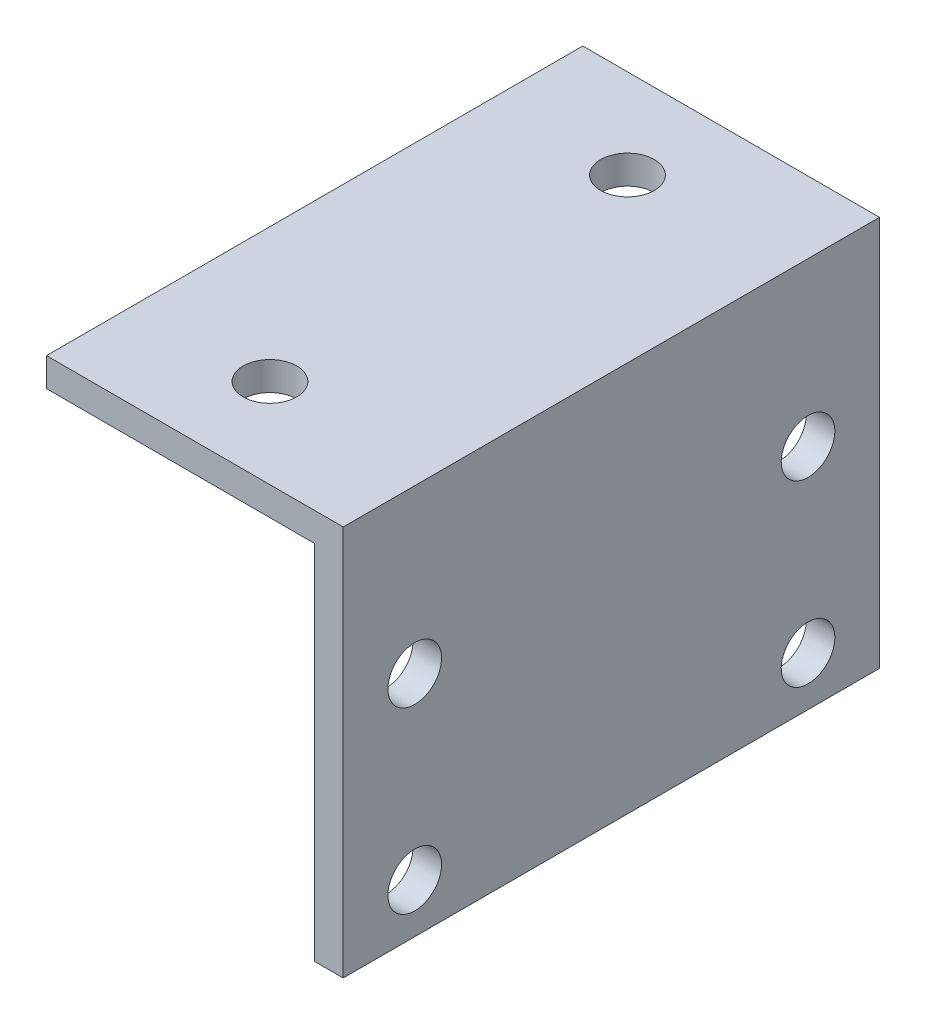
SolidWorks part; units mm, degrees
ref_plane "Front Plane" through (0, 0, 0) normal (0, 0, 1) x (1, 0, 0)
ref_plane "Top Plane" through (0, 0, 0) normal (0, 1, 0) x (1, 0, 0)
ref_plane "Right Plane" through (0, 0, 0) normal (1, 0, 0) x (0, 0, -1)
sketch "Sketch1" plane through (0, 0, 0) normal (0, 0, 1) x (1, 0, 0)
  line L0 (0, 0) -> (-23.4, 0)
  line L1 (-23.4, 0) -> (-23.4, 1.6)
  line L2 (-23.4, 1.6) -> (1.6, 1.6)
  line L3 (1.6, 1.6) -> (1.6, -23.4)
  line L4 (1.6, -23.4) -> (0, -23.4)
  line L5 (0, -23.4) -> (0, 0)
  dimension "D1" = 25
  dimension "D2" = 1.6
extrude "Angle" add sketch "Sketch1" along normal blind 30
sketch "Sketch2" plane through (0, 0, 0) normal (0, -1, 0) x (1, 0, 0)
  line L0 (-7.5, 0) -> (-7.5, 5) construction
  line L1 (-23.4, 0) -> (0, 0) construction
  line L4 (-7.5, 5) -> (-7.5, 25) construction
  line L5 (-7.5, 25) -> (-7.5, 30) construction
  line L6 (-23.4, 30) -> (0, 30) construction
  circle A0 centre (-7.5, 5) radius 1.5
  circle A1 centre (-7.5, 25) radius 1.5
  dimension "D2" = 3
  dimension "D1" = 7.5
  dimension "D3" = 5
extrude "Cut-Extrude1" cut sketch "Sketch2" against normal blind 50
sketch "Sketch3" plane through (0, 0, 0) normal (-1, 0, 0) x (0, 0, 1)
  line L0 (0, -7.5) -> (4, -7.5) construction
  line L2 (0, 0) -> (0, -23.4) construction
  line L4 (26, -7.5) -> (30, -7.5) construction
  line L5 (30, 0) -> (30, -23.4) construction
  line L6 (4, -7.5) -> (26, -7.5) construction
  line L7 (4, -7.5) -> (4, -17.5) construction
  line L8 (4, -17.5) -> (26, -17.5) construction
  line L9 (26, -7.5) -> (26, -17.5) construction
  circle A0 centre (4, -7.5) radius 1.5
  circle A1 centre (26, -7.5) radius 1.5
  circle A2 centre (4, -17.5) radius 1.5
  circle A3 centre (26, -17.5) radius 1.5
  dimension "D1" = 3
  dimension "D2" = 22
  dimension "D3" = 7.5
  dimension "D4" = 10
extrude "Cut-Extrude2" cut sketch "Sketch3" against normal blind 50
sketch "Sketch4" plane through (0, 0, 0) normal (-1, 0, 0) x (0, 0, 1)
  line L0 (4, -7.5) -> (26, -17.5) construction
  line L2 (30, -20.25) -> (0, -20.25) construction
  line L3 (30, -20.25) -> (30, -4.75) construction
  line L4 (30, -4.75) -> (0, -4.75) construction
  line L5 (0, -20.25) -> (0, -4.75) construction
  line L6 (30, -20.25) -> (0, -4.75) construction
  line L7 (30, -4.75) -> (0, -20.25) construction
  line L8 (0, -20.25) -> (30, -20.25)
  line L9 (0, -20.25) -> (0, -23.4)
  line L10 (0, -23.4) -> (30, -23.4)
  line L11 (30, -20.25) -> (30, -23.4)
  circle A0 centre (4, -17.5) radius 1.5 construction
  circle A1 centre (26, -17.5) radius 1.5 construction
  circle A2 centre (26, -7.5) radius 1.5 construction
  circle A3 centre (4, -7.5) radius 1.5 construction
  circle A4 centre (4, -17.5) radius 1.5 construction
  circle A5 centre (26, -17.5) radius 1.5 construction
  circle A6 centre (26, -7.5) radius 1.5 construction
  circle A7 centre (4, -7.5) radius 1.5 construction
  point P12 (15, -12.5)
  dimension "D1" = 15.5
extrude "Cut-Extrude3" cut sketch "Sketch4" against normal blind 50
sketch "Sketch5" plane through (0, 0, 0) normal (0, -1, 0) x (1, 0, 0)
  line L0 (-23.4, 0) -> (0, 0) construction
  line L1 (-23.4, 30) -> (-15, 30)
  line L2 (-23.4, 30) -> (-23.4, 0)
  line L3 (-23.4, 0) -> (-15, 0)
  line L4 (-15, 30) -> (-15, 0)
  dimension "D1" = 15
extrude "Cut-Extrude4" cut sketch "Sketch5" against normal blind 50
